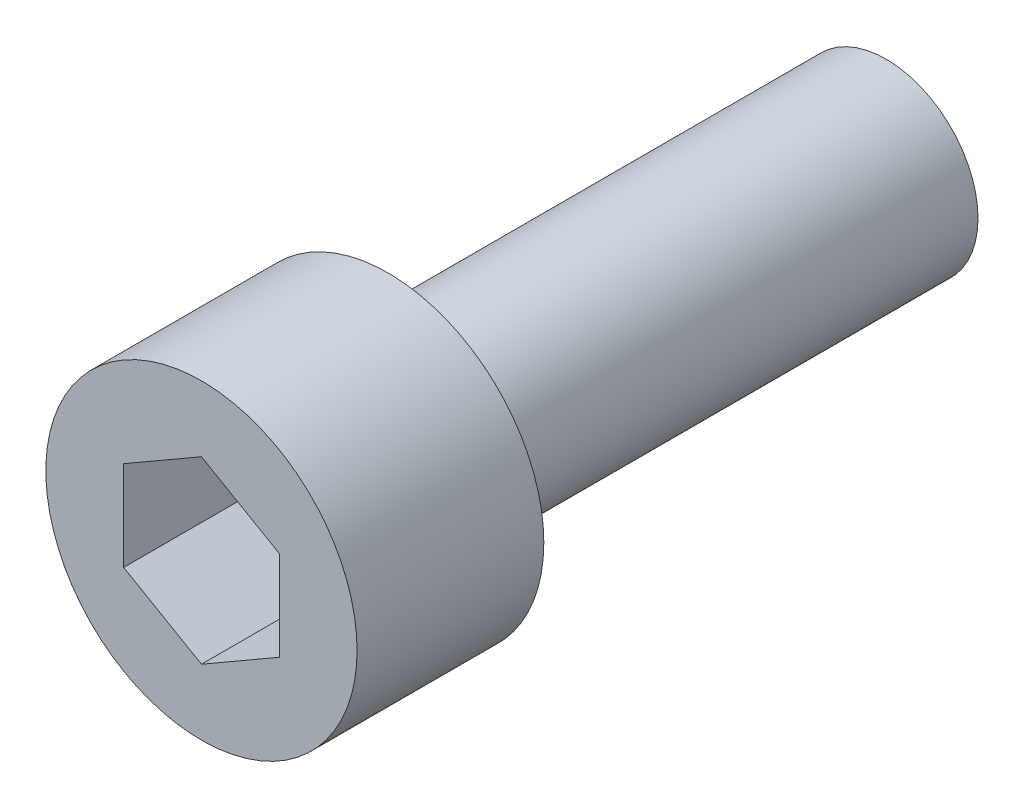
SolidWorks part; units mm, degrees
ref_plane "前视基准面" through (0, 0, 0) normal (0, 0, 1) x (1, 0, 0)
ref_plane "上视基准面" through (0, 0, 0) normal (0, 1, 0) x (1, 0, 0)
ref_plane "右视基准面" through (0, 0, 0) normal (1, 0, 0) x (0, 0, -1)
other "Configuration Table"
sketch "草图1" plane through (0, 0, 0) normal (0, 0, 1) x (1, 0, 0)
  circle A0 centre (0, 0) radius 2.95
extrude "Shank_threads_simplified" add sketch "草图1" against normal blind 16
sketch "草图2" plane through (0, 0, 0) normal (0, 0, 1) x (1, 0, 0)
  circle A0 centre (0, 0) radius 5
extrude "Socket_head" add sketch "草图2" along normal blind 6
ref_plane "Plane_z_6_2" through (0, 0, 6) normal (0, 0, 1) x (1, 0, 0)
sketch "草图3" plane through (0, 0, 6) normal (0, 0, 1) x (1, 0, 0)
  line L0 (2.5, 1.4434) -> (0, 2.8868)
  line L1 (0, 2.8868) -> (-2.5, 1.4434)
  line L2 (-2.5, 1.4434) -> (-2.5, -1.4434)
  line L3 (-2.5, -1.4434) -> (0, -2.8868)
  line L4 (0, -2.8868) -> (2.5, -1.4434)
  line L5 (2.5, -1.4434) -> (2.5, 1.4434)
extrude "Hex_socket" cut sketch "草图3" against normal blind 3.9
